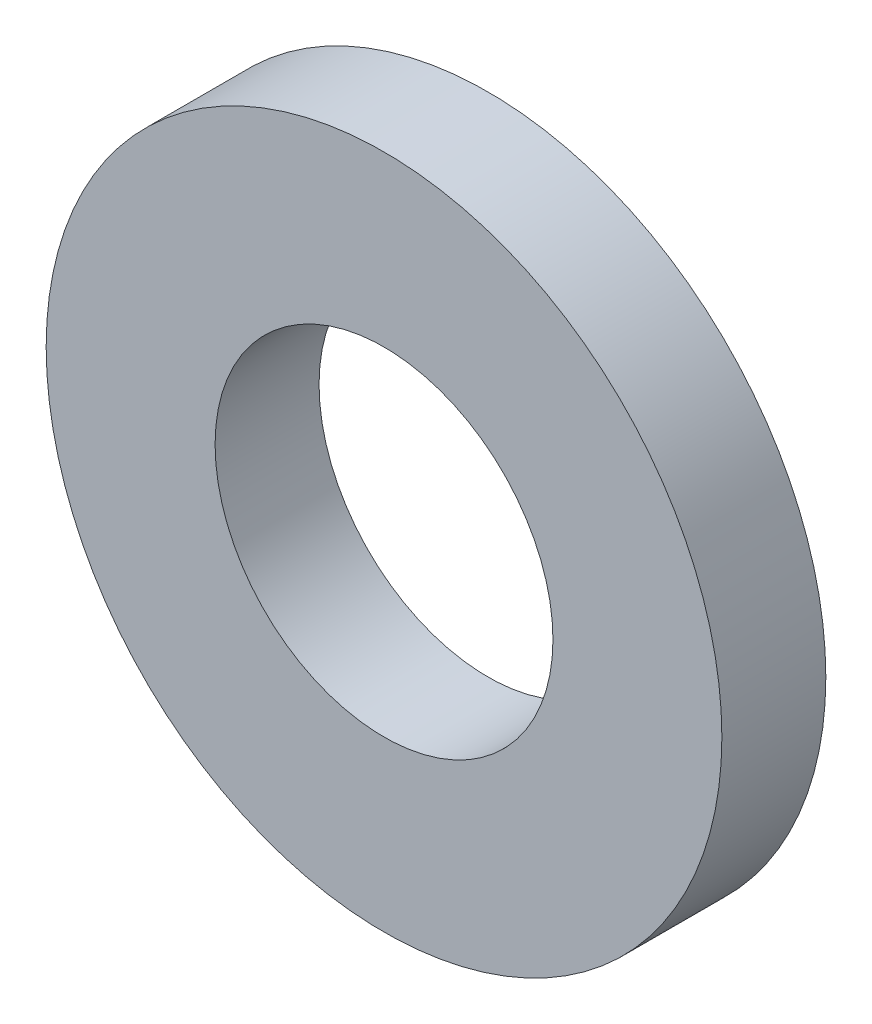
SolidWorks part; units mm, degrees
material "AISI 1020"
ref_plane "Front Plane" through (0, 0, 0) normal (0, 0, 1) x (1, 0, 0)
ref_plane "Top Plane" through (0, 0, 0) normal (0, 1, 0) x (1, 0, 0)
ref_plane "Right Plane" through (0, 0, 0) normal (1, 0, 0) x (0, 0, -1)
sketch "Sketch1" plane through (0, 0, 0) normal (0, 0, 1) x (1, 0, 0)
  circle A0 centre (0, 0) radius 3.25
  circle A1 centre (0, 0) radius 6.5
  dimension "D1" = 6.5
  dimension "D2" = 13
extrude "Boss-Extrude1" add sketch "Sketch1" along normal blind 2
